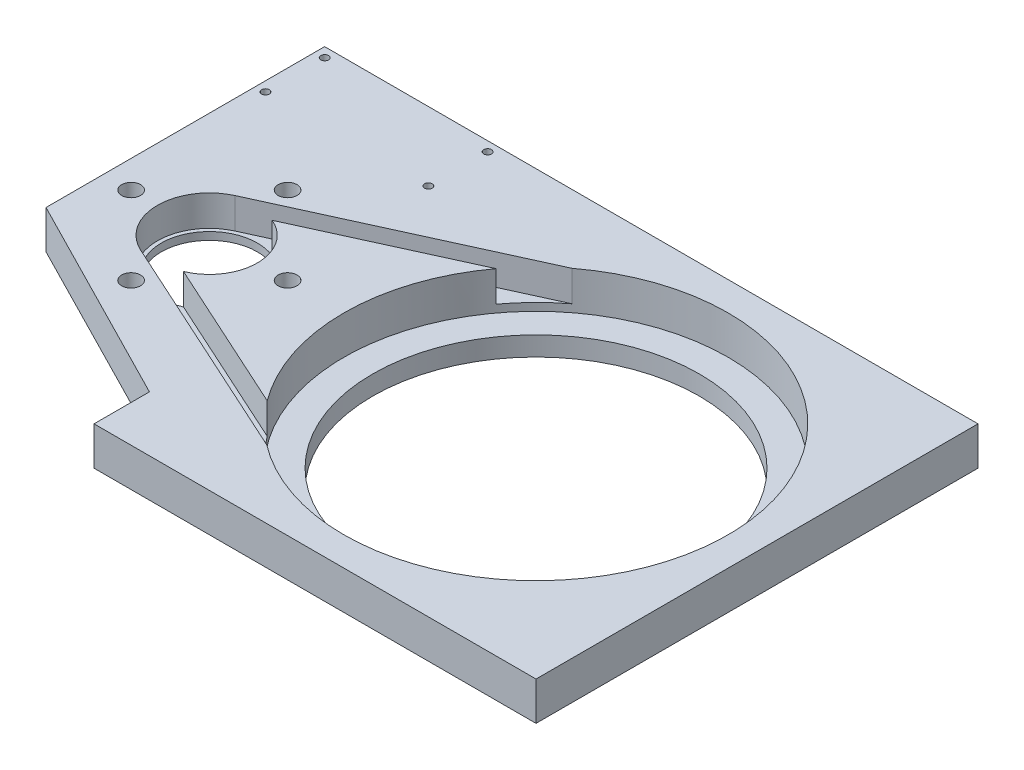
SolidWorks part; units mm, degrees
material "ABS"
ref_plane "Front Plane" through (0, 0, 0) normal (0, 0, 1) x (1, 0, 0)
ref_plane "Top Plane" through (0, 0, 0) normal (0, 1, 0) x (1, 0, 0)
ref_plane "Right Plane" through (0, 0, 0) normal (1, 0, 0) x (0, 0, -1)
sketch "Sketch1" plane through (0, 0, 0) normal (0, 1, 0) x (1, 0, 0)
  line L1 (-52.5, -52.5) -> (52.5, -52.5)
  line L2 (-52.5, -52.5) -> (-52.5, 52.5)
  line L3 (-52.5, 52.5) -> (52.5, 52.5)
  line L4 (52.5, -52.5) -> (52.5, 52.5)
  point P4 (0, -52.5)
  point P6 (-52.5, 0)
  dimension "D1" = 105
extrude "Boss-Extrude1" add sketch "Sketch1" along normal blind 5 contours L3 L4 L1 L2
sketch "Sketch2" plane through (0, 5, 0) normal (0, 1, 0) x (1, 0, 0)
  line L0 (52.5, -52.5) -> (52.5, 52.5) construction
  line L1 (-57.5, -57.5) -> (57.5, -57.5)
  line L2 (-57.5, -57.5) -> (-57.5, 57.5)
  line L3 (-57.5, 57.5) -> (57.5, 57.5)
  line L4 (57.5, -57.5) -> (57.5, 57.5)
  point P4 (0, -57.5)
  point P6 (-57.5, 0)
  dimension "D1" = 5
extrude "Boss-Extrude2" add sketch "Sketch2" along normal blind 10
sketch "Sketch3" plane through (0, 15, 0) normal (0, 1, 0) x (1, 0, 0)
  circle A0 centre (0, 0) radius 42.5
  dimension "D1" = 85
extrude "Cut-Extrude1" cut sketch "Sketch3" against normal through all
sketch "Sketch4" plane through (0, 15, 0) normal (0, 1, 0) x (1, 0, 0)
  circle A0 centre (0, 0) radius 50
  dimension "D1" = 100
extrude "Cut-Extrude2" cut sketch "Sketch4" against normal offset from surface (10 mm away) 5 up to face at (0, 0, 42.5)
sketch "Sketch5" plane through (0, 15, 0) normal (0, 1, 0) x (1, 0, 0)
  line L0 (-57.5, 57.5) -> (-57.5, -57.5) construction
  line L2 (-57.5, 43.0904) -> (-57.5, -43.0904)
  line L5 (-57.5, 43.0904) -> (-112.5, 15)
  line L6 (-112.5, 15) -> (-112.5, -15)
  line L7 (-112.5, -15) -> (-57.5, -43.0904)
  point P6 (-57.5, 0)
  point P8 (-112.5, 0)
  dimension "D1" = 30
  dimension "D2" = 55
  dimension "D3" = 54.11
extrude "Boss-Extrude3" add sketch "Sketch5" against normal up to surface (10 mm away) up to face at (0, 5, 0)
sketch "Sketch6" plane through (0, 15, 0) normal (0, 1, 0) x (1, 0, 0)
  circle A0 centre (-85, 0) radius 12.5
  point P2 (0, 0)
  point P3 (0, 0)
  dimension "D1" = 25
  dimension "D2" = 85
extrude "Cut-Extrude3" cut sketch "Sketch6" against normal through all
hole_wizard "#8 Clearance Hole1" positions "Sketch7" profile "Sketch8" hole size "#8" standard "ANSI Inch" end condition through all
sketch "Sketch7" plane through (0, 5, 0) normal (0, -1, 0) x (-1, 0, 0)
  line L0 (105.3576, 0) -> (64.6424, 0) construction
  line L1 (85, 20.3576) -> (85, -20.3576) construction
  line L2 (85, 0) -> (64.6424, 0) construction
  point P0 (64.6424, 0)
  point P2 (85, -20.3576)
  point P4 (105.3576, 0)
  point P6 (85, 20.3576)
  point P15 (85, 0)
  point P16 (85, 0)
  dimension "D1" = 40.7152
sketch "Sketch8" plane through (-64.6424, 5, 0) normal (1, 0, 0) x (0, 0, -1)
  line L0 (0, 0) -> (0, 10)
  line L1 (0, 10) -> (2.4574, 10)
  line L2 (2.4574, 10) -> (2.4574, 0)
  line L5 (2.4574, 0) -> (0, 0)
  line L11 (0, -6.35) -> (0, 107.95) construction
  dimension "Thru Hole Dia." = 4.9149
  dimension "Thru Hole Depth" = 10
sketch "Sketch9" plane through (0, 15, 0) normal (0, 1, 0) x (1, 0, 0)
  line L0 (-19.1801, 42.0854) -> (-89.5618, 10.0095) construction
  line L1 (-19.1801, -42.0854) -> (-89.5618, -10.0095) construction
  line L2 (-20.2169, 44.3603) -> (-90.5985, 12.2844)
  line L3 (-18.1434, -39.8106) -> (-88.525, -7.7346)
  line L4 (-18.1434, 39.8106) -> (-88.525, 7.7346)
  line L5 (-20.2169, -44.3603) -> (-90.5985, -12.2844)
  circle A0 centre (0, 0) radius 46.25 construction
  circle A1 centre (-85, 0) radius 11 construction
  arc A2 (-20.2169, 44.3603) -> (-18.1434, 39.8106) centre (-19.1801, 42.0854) cw
  arc A4 (-18.1434, -39.8106) -> (-20.2169, -44.3603) centre (-19.1801, -42.0854) cw
  arc A6 (-90.5985, -12.2844) -> (-90.5985, 12.2844) centre (-85, 0) cw
  arc A7 (-88.525, -7.7346) -> (-88.525, 7.7346) centre (-85, 0) cw
  dimension "D1" = 92.5
  dimension "D2" = 22
  dimension "D3" = 2.5
extrude "Cut-Extrude4" cut sketch "Sketch9" against normal blind 8
sketch "Sketch10" plane through (0, 15, 0) normal (0, 1, 0) x (1, 0, 0)
  line L0 (-57.5, 57.5) -> (-112.5, 57.5)
  line L1 (-57.5, 57.5) -> (-57.5, 43.0904) construction
  line L2 (-112.5, 57.5) -> (-112.5, 15)
  line L3 (-57.5, 43.0904) -> (-112.5, 15) construction
  line L4 (-112.5, 15) -> (-57.5, 43.0904)
  line L5 (-57.5, 43.0904) -> (-57.5, 57.5)
  line L7 (-110, 55) -> (-67.6, 55) construction
  line L8 (-67.6, 55) -> (-67.6, 39.6) construction
  line L9 (-67.6, 39.6) -> (-110, 39.6) construction
  line L10 (-110, 39.6) -> (-110, 55) construction
  line L11 (57.5, 57.5) -> (-57.5, 57.5) construction
  line L12 (-112.5, 15) -> (-112.5, -15) construction
  circle A0 centre (-67.6, 55) radius 1
  circle A1 centre (-67.6, 39.6) radius 1
  circle A2 centre (-110, 55) radius 1
  circle A3 centre (-110, 39.6) radius 1
  point P21 (-93.5107, 52.5)
  dimension "D3" = 2
  dimension "D6" = 2.5
  dimension "D4" = 42.4
  dimension "D5" = 15.4
  dimension "D7" = 2.5
extrude "Boss-Extrude4" add sketch "Sketch10" against normal blind 2
